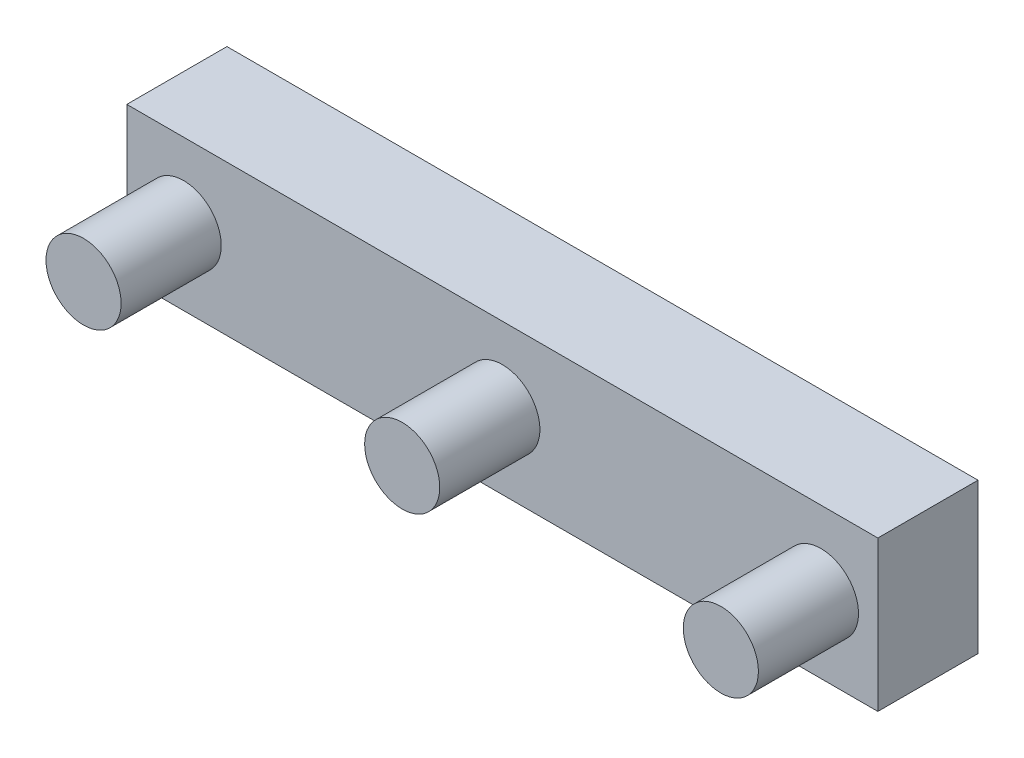
SolidWorks part; units mm, degrees
ref_plane "Front" through (0, 0, 0) normal (0, 0, 1) x (1, 0, 0)
ref_plane "Top" through (0, 0, 0) normal (0, 1, 0) x (1, 0, 0)
ref_plane "Right" through (0, 0, 0) normal (1, 0, 0) x (0, 0, -1)
sketch "Sketch1" plane through (0, 0, 0) normal (0, 0, 1) x (1, 0, 0)
  line L1 (-37.5, -7.5) -> (37.5, -7.5)
  line L2 (-37.5, -7.5) -> (-37.5, 7.5)
  line L3 (-37.5, 7.5) -> (37.5, 7.5)
  line L4 (37.5, -7.5) -> (37.5, 7.5)
  point P4 (46.5111, 18.8886)
  point P5 (0, 7.5)
  point P7 (-37.5, 0)
  dimension "D1" = 75
  dimension "D2" = 15
extrude "Boss-Extrude1" add sketch "Sketch1" along normal blind 10
sketch "Sketch2" plane through (0, 0, 10) normal (0, 0, 1) x (1, 0, 0)
  line L0 (37.5, -7.5) -> (37.5, 7.5) construction
  line L1 (-31.8198, 0) -> (0, 0) construction
  line L2 (0, 0) -> (31.8198, 0) construction
  circle A0 centre (0, 0) radius 3.75
  circle A1 centre (-31.8198, 0) radius 3.75
  circle A2 centre (31.8198, 0) radius 3.75
  point P9 (37.5, 0)
  dimension "D1" = 7.5
  dimension "D2" = 31.8198
extrude "Boss-Extrude2" add sketch "Sketch2" along normal blind 10
